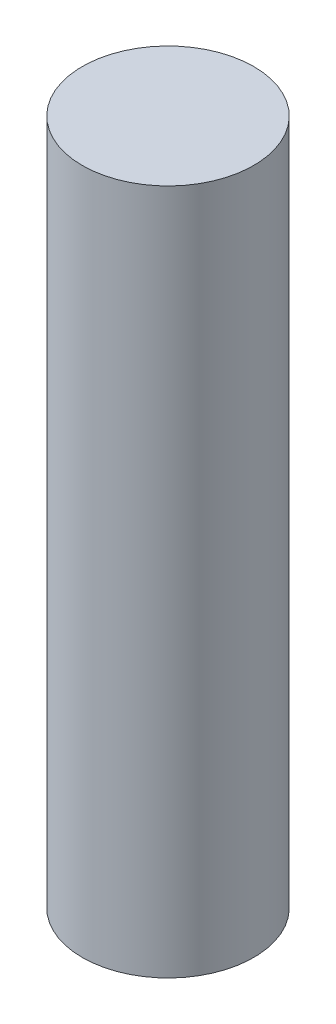
SolidWorks part; units mm, degrees
ref_plane "Plan de face" through (0, 0, 0) normal (0, 0, 1) x (1, 0, 0)
ref_plane "Plan de dessus" through (0, 0, 0) normal (0, 1, 0) x (1, 0, 0)
ref_plane "Plan de droite" through (0, 0, 0) normal (1, 0, 0) x (0, 0, -1)
sketch "Esquisse1" plane through (0, 0, 0) normal (0, 1, 0) x (1, 0, 0)
  circle A0 centre (0, 0) radius 12.5
  dimension "D1" = 25
extrude "Boss.-Extru.1" add sketch "Esquisse1" along normal blind 100
